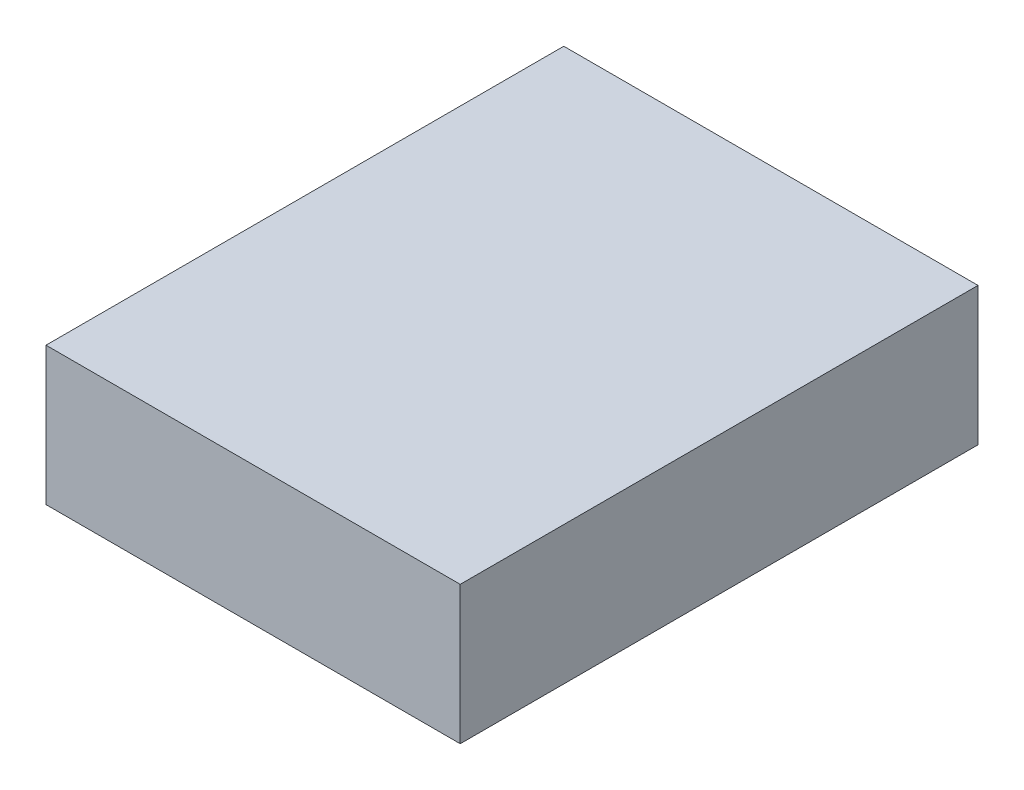
SolidWorks part; units mm, degrees
ref_plane "Front Plane" through (0, 0, 0) normal (0, 0, 1) x (1, 0, 0)
ref_plane "Top Plane" through (0, 0, 0) normal (0, 1, 0) x (1, 0, 0)
ref_plane "Right Plane" through (0, 0, 0) normal (1, 0, 0) x (0, 0, -1)
sketch "Sketch1" plane through (0, 0, 0) normal (0, 1, 0) x (1, 0, 0)
  line L1 (-30, -37.5) -> (30, -37.5)
  line L2 (-30, -37.5) -> (-30, 37.5)
  line L3 (-30, 37.5) -> (30, 37.5)
  line L4 (30, -37.5) -> (30, 37.5)
  line L5 (-30, -37.5) -> (30, 37.5) construction
  line L6 (-30, 37.5) -> (30, -37.5) construction
  point P0 (0, 0)
  dimension "D1" = 75
  dimension "D2" = 60
extrude "Boss-Extrude1" add sketch "Sketch1" along normal blind 20
